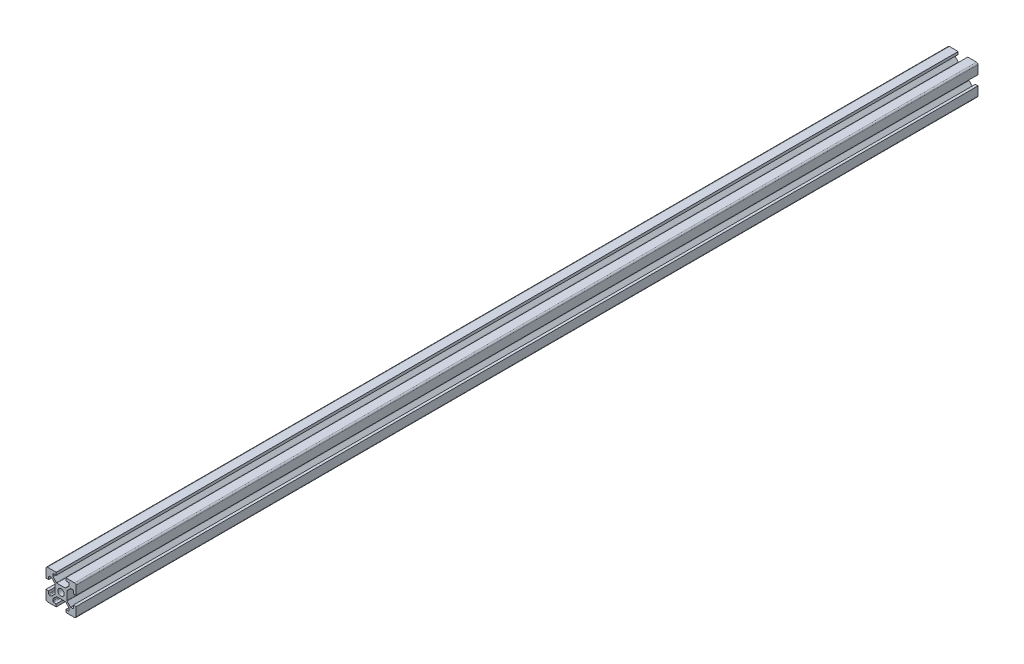
SolidWorks part; units mm, degrees
material "1060 Alloy"
ref_plane "Front Plane" through (0, 0, 0) normal (0, 0, 1) x (1, 0, 0)
ref_plane "Top Plane" through (0, 0, 0) normal (0, 1, 0) x (1, 0, 0)
ref_plane "Right Plane" through (0, 0, 0) normal (1, 0, 0) x (0, 0, -1)
sketch "Sketch1" plane through (0, 0, 0) normal (0, 0, 1) x (1, 0, 0)
  line L0 (20, 0) -> (-8.059, 28.059) construction
  line L1 (0, 0) -> (6.8, 0)
  line L2 (0, 0) -> (0, 6.8)
  line L3 (0, 20) -> (6.8, 20)
  line L4 (20, 0) -> (20, 6.8)
  line L5 (6.8, 20) -> (6.8, 18.2)
  line L6 (20, 20) -> (8.5151, 8.5151) construction
  line L7 (12.95, 6.1) -> (7.05, 6.1)
  line L8 (13.9, 7.05) -> (13.9, 12.95)
  line L9 (12.95, 13.9) -> (7.05, 13.9)
  line L10 (6.1, 7.05) -> (6.1, 12.95)
  line L11 (13.9, 6.1) -> (6.1, 13.9) construction
  line L12 (13.9, 13.9) -> (6.1, 6.1) construction
  line L13 (4.55, 16.4) -> (7.05, 13.9)
  line L14 (13.2, 18.2) -> (13.2, 20)
  line L15 (1.8, 6.8) -> (0, 6.8)
  line L16 (0, 13.2) -> (0, 20)
  line L17 (0, 13.2) -> (1.8, 13.2)
  line L18 (10, 10) -> (10, 13.9) construction
  line L19 (16.4, 4.55) -> (13.9, 7.05)
  line L20 (4.55, 16.4) -> (4.55, 18.2)
  line L21 (4.55, 18.2) -> (6.8, 18.2)
  line L22 (13.2, 18.2) -> (15.45, 18.2)
  line L23 (15.45, 18.2) -> (15.45, 16.4)
  line L24 (15.45, 16.4) -> (12.95, 13.9)
  line L25 (16.4, 4.55) -> (18.2, 4.55)
  line L26 (18.2, 4.55) -> (18.2, 6.8)
  line L27 (20, 6.8) -> (18.2, 6.8)
  line L28 (18.2, 13.2) -> (20, 13.2)
  line L29 (18.2, 13.2) -> (18.2, 15.45)
  line L30 (18.2, 15.45) -> (16.4, 15.45)
  line L31 (16.4, 15.45) -> (13.9, 12.95)
  line L32 (1.8, 4.55) -> (3.6, 4.55)
  line L33 (3.6, 15.45) -> (6.1, 12.95)
  line L34 (3.6, 15.45) -> (1.8, 15.45)
  line L35 (1.8, 15.45) -> (1.8, 13.2)
  line L36 (0, 13.2) -> (1.8, 13.2)
  line L37 (1.8, 6.8) -> (0, 6.8)
  line L38 (3.6, 4.55) -> (6.1, 7.05)
  line L39 (1.8, 6.8) -> (1.8, 4.55)
  line L40 (15.45, 3.6) -> (12.95, 6.1)
  line L41 (4.55, 3.6) -> (7.05, 6.1)
  line L42 (4.55, 1.8) -> (4.55, 3.6)
  line L43 (6.8, 1.8) -> (4.55, 1.8)
  line L44 (6.8, 1.8) -> (6.8, 0)
  line L45 (15.45, 3.6) -> (15.45, 1.8)
  line L46 (15.45, 1.8) -> (13.2, 1.8)
  line L47 (13.2, 0) -> (13.2, 1.8)
  line L48 (13.2, 20) -> (20, 20)
  line L49 (20, 13.2) -> (20, 20)
  line L50 (13.2, 0) -> (20, 0)
  line L51 (6.1, 6.1) -> (-5.5045, -5.5045) construction
  circle A0 centre (10, 10) radius 2.1
  point P25 (10, 16.4)
  point P39 (13.2, 19.1)
  point P46 (0.9, 6.8)
  dimension "D3" = 4.2
  dimension "D2" = 20
  dimension "D4" = 7.8
  dimension "D5" = 7.8
  dimension "D6" = 6.8
  dimension "D7" = 6.8
  dimension "D8" = 1.8
  dimension "D9" = 10.9
  dimension "D10" = 1.8
  dimension "D11" = 10.9
  dimension "D12" = 20
extrude "Boss-Extrude1" add sketch "Sketch1" along normal blind 600 contours L47 L50 L4 L27 L26 L25 L19 L8 L31 L30 L29 L28 L49 L48 L14 L22 L23 L24 L9 L13 L20 L21 L5 L3 L16 L17 L35 L34 L33 L10 L38 L32 L39 L15 L2 L1 L44 L43 L42 L41 L7 L40 L45 L46 A0
fillet "Fillet1" radius 1 4 edges at (20, 20, 300) (20, 0, 300) (0, 0, 300) (0, 20, 300)
fillet "Fillet2" radius 0.5 6 edges at (4.55, 18.2, 300) (4.55, 16.4, 300) (7.05, 13.9, 300) (15.45, 18.2, 300) (15.45, 16.4, 300) (12.95, 13.9, 300)
fillet "Fillet3" radius 0.5 6 edges at (18.2, 15.45, 300) (16.4, 15.45, 300) (13.9, 12.95, 300) (18.2, 4.55, 300) (13.9, 7.05, 300) (16.4, 4.55, 300)
fillet "Fillet4" radius 0.5 6 edges at (1.8, 15.45, 300) (3.6, 15.45, 300) (6.1, 12.95, 300) (3.6, 4.55, 300) (1.8, 4.55, 300) (6.1, 7.05, 300)
fillet "Fillet5" radius 0.5 6 edges at (7.05, 6.1, 300) (4.55, 3.6, 300) (4.55, 1.8, 300) (15.45, 1.8, 300) (15.45, 3.6, 300) (12.95, 6.1, 300)
